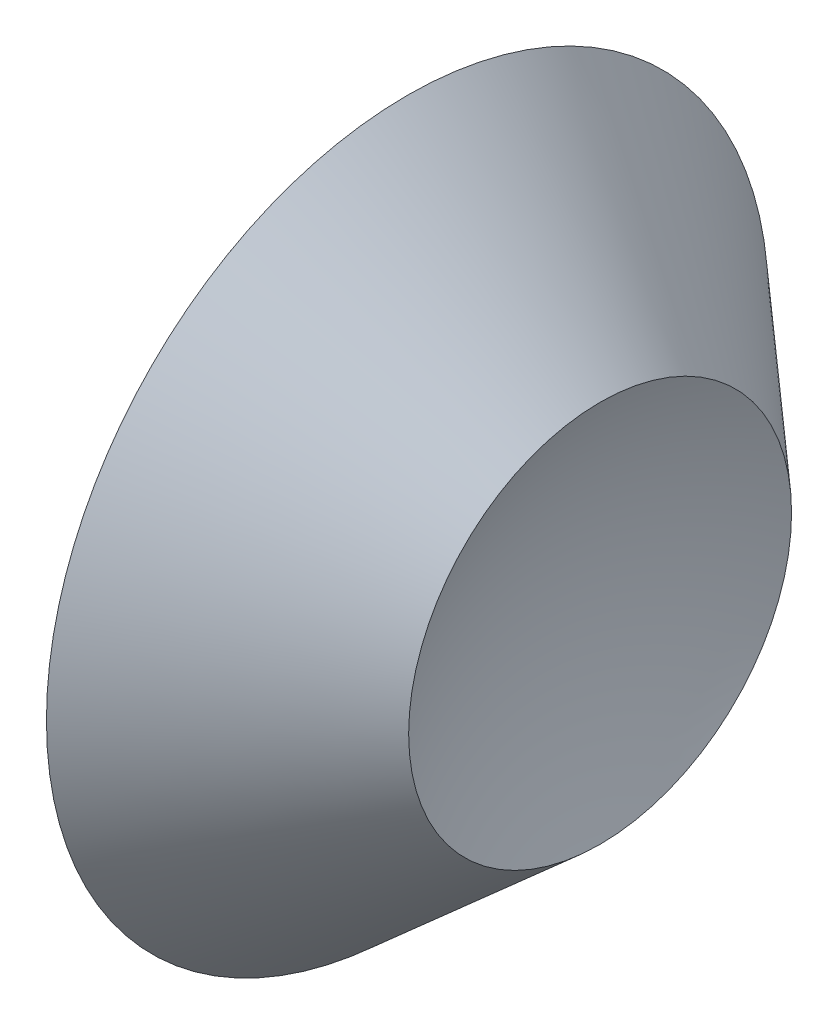
SolidWorks part; units mm, degrees
material "玻璃"
ref_plane "前视基准面" through (0, 0, 0) normal (0, 0, 1) x (1, 0, 0)
ref_plane "上视基准面" through (0, 0, 0) normal (0, 1, 0) x (1, 0, 0)
ref_plane "右视基准面" through (0, 0, 0) normal (1, 0, 0) x (0, 0, -1)
sketch "草图1" plane through (0, 0, 0) normal (0, 0, 1) x (1, 0, 0)
  line L0 (-55, 0) -> (-53.3676, 0)
  line L3 (-52.9992, 1.8756) -> (-54.8862, 3.5369)
  arc A0 (-54.8862, 3.5369) -> (-55, 0) centre (0, 0) ccw
  arc A2 (-52.9992, 1.8756) -> (-53.3676, 0) centre (-48.4079, 0) ccw
revolve "旋转1" add sketch "草图1" angle 360 about L0
